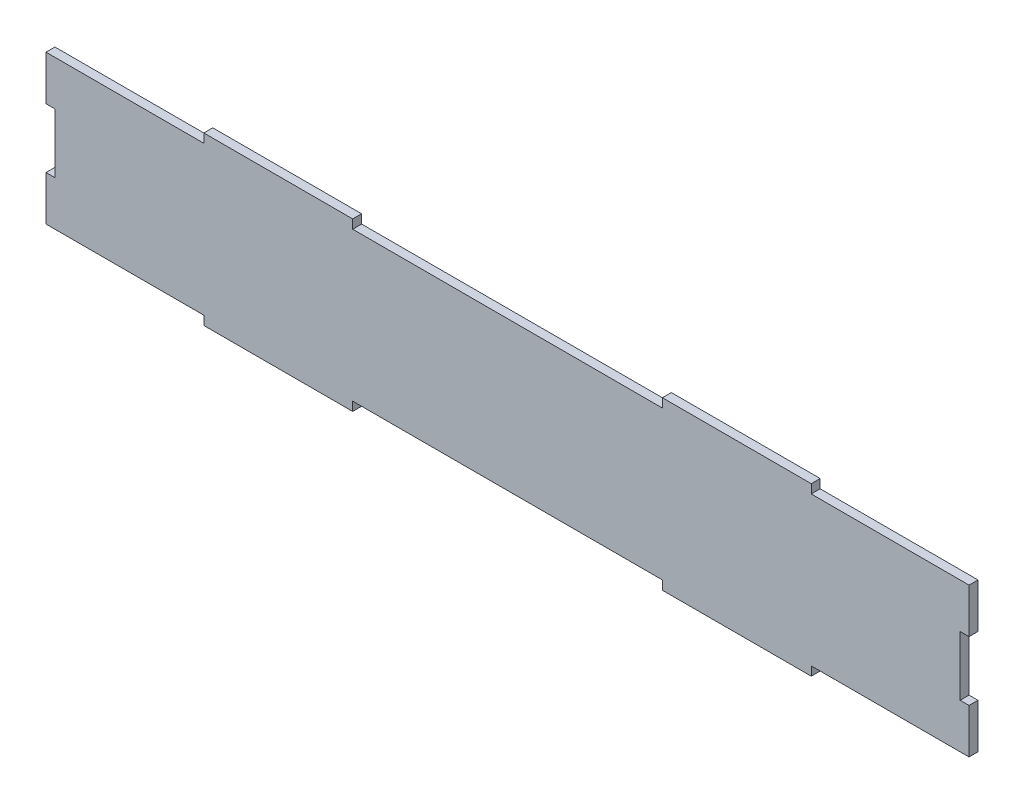
SolidWorks part; units mm, degrees
material "아크릴(내충격성)"
ref_plane "정면" through (0, 0, 0) normal (0, 0, 1) x (1, 0, 0)
ref_plane "윗면" through (0, 0, 0) normal (0, 1, 0) x (1, 0, 0)
ref_plane "우측면" through (0, 0, 0) normal (1, 0, 0) x (0, 0, -1)
sketch "스케치1" plane through (0, 0, 0) normal (0, 0, 1) x (1, 0, 0)
  line L0 (-102, 25) -> (-102, -25) construction
  line L1 (-152, 25) -> (-102, 25)
  line L2 (-152, 10) -> (-152, -10)
  line L3 (-152, -25) -> (-102, -25)
  line L4 (152, 10) -> (152, -10)
  line L5 (-152, 25) -> (152, -25) construction
  line L6 (-152, -25) -> (152, 25) construction
  line L7 (-52, 25) -> (-52, -25) construction
  line L8 (52, 25) -> (52, -25) construction
  line L9 (102, 25) -> (102, -25) construction
  line L10 (-152, 10) -> (152, 10) construction
  line L11 (-152, -10) -> (152, -10) construction
  line L12 (-102, 25) -> (-102, 28)
  line L13 (-102, 28) -> (-52, 28)
  line L14 (-52, 28) -> (-52, 25)
  line L15 (52, 25) -> (52, 28)
  line L16 (52, 28) -> (102, 28)
  line L17 (102, 28) -> (102, 25)
  line L18 (-102, -25) -> (-102, -28)
  line L19 (-102, -28) -> (-52, -28)
  line L20 (-52, -28) -> (-52, -25)
  line L21 (52, -25) -> (52, -28)
  line L22 (52, -28) -> (102, -28)
  line L23 (102, -28) -> (102, -25)
  line L24 (-152, 25) -> (-155, 25)
  line L25 (-155, 25) -> (-155, 10)
  line L26 (-155, 10) -> (-152, 10)
  line L27 (-152, -10) -> (-155, -10)
  line L28 (-155, -10) -> (-155, -25)
  line L29 (-155, -25) -> (-152, -25)
  line L30 (152, -10) -> (155, -10)
  line L31 (155, -10) -> (155, -25)
  line L32 (155, -25) -> (152, -25)
  line L33 (152, 25) -> (155, 25)
  line L34 (155, 25) -> (155, 10)
  line L35 (155, 10) -> (152, 10)
  line L36 (-52, -25) -> (52, -25)
  line L37 (-52, 25) -> (52, 25)
  line L38 (102, 25) -> (152, 25)
  line L39 (102, -25) -> (152, -25)
  point P0 (0, 0)
  dimension "D1" = 304
  dimension "D2" = 50
  dimension "D3" = 15
  dimension "D4" = 15
  dimension "D5" = 50
  dimension "D6" = 50
  dimension "D7" = 50
  dimension "D8" = 50
  dimension "D9" = 3
  dimension "D10" = 3
  dimension "D11" = 3
  dimension "D12" = 3
  dimension "D13" = 3
  dimension "D14" = 3
  dimension "D15" = 3
  dimension "D16" = 3
extrude "보스-돌출1" add sketch "스케치1" along normal blind 3
